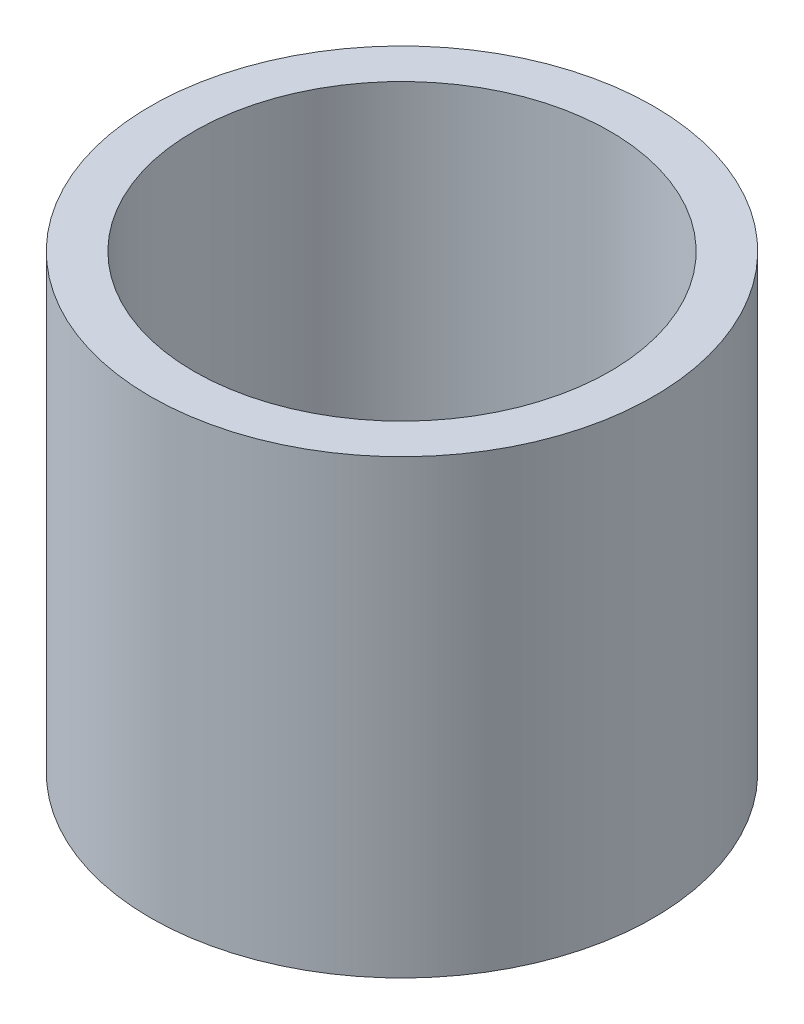
SolidWorks part; units mm, degrees
ref_plane "Front Plane" through (0, 0, 0) normal (0, 0, 1) x (1, 0, 0)
ref_plane "Top Plane" through (0, 0, 0) normal (0, 1, 0) x (1, 0, 0)
ref_plane "Right Plane" through (0, 0, 0) normal (1, 0, 0) x (0, 0, -1)
sketch "Sketch1" plane through (0, 0, 0) normal (0, 1, 0) x (1, 0, 0)
  circle A0 centre (0, 0) radius 3.225
  circle A1 centre (0, 0) radius 3.9
  dimension "D1" = 6.45
  dimension "D2" = 7.8
extrude "Boss-Extrude1" add sketch "Sketch1" along normal blind 7
